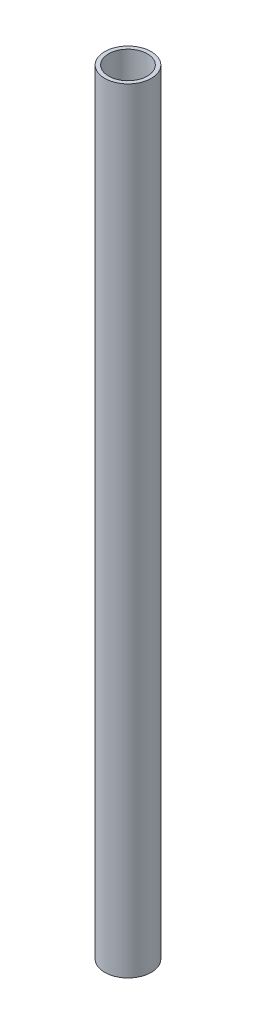
SolidWorks part; units mm, degrees
material "Hexcel AS4C (3000 丝)"
ref_plane "前视基准面" through (0, 0, 0) normal (0, 0, 1) x (1, 0, 0)
ref_plane "上视基准面" through (0, 0, 0) normal (0, 1, 0) x (1, 0, 0)
ref_plane "右视基准面" through (0, 0, 0) normal (1, 0, 0) x (0, 0, -1)
sketch "草图1" plane through (0, 0, 0) normal (0, 1, 0) x (1, 0, 0)
  circle A0 centre (0, 0) radius 6
  circle A1 centre (0, 0) radius 5
  dimension "D1" = 12
  dimension "D2" = 10
extrude "凸台-拉伸1" add sketch "草图1" along normal blind 200
